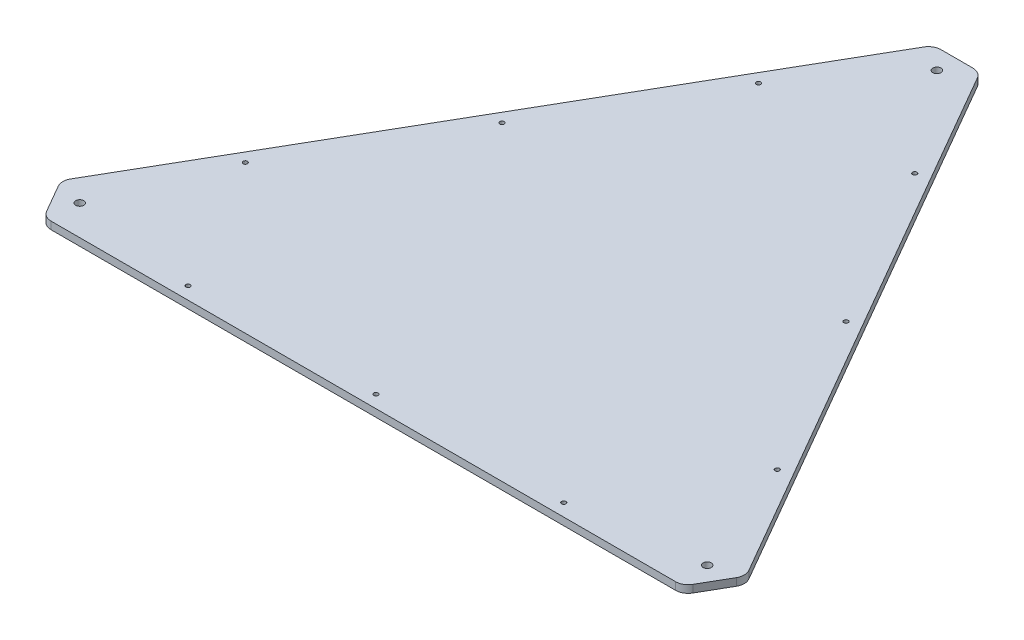
SolidWorks part; units mm, degrees
material "ABS"
ref_plane "Спереди" through (0, 0, 0) normal (0, 0, 1) x (1, 0, 0)
ref_plane "Сверху" through (0, 0, 0) normal (0, 1, 0) x (1, 0, 0)
ref_plane "Справа" through (0, 0, 0) normal (1, 0, 0) x (0, 0, -1)
sketch "Эскиз1" plane through (0, 0, 0) normal (0, 1, 0) x (1, 0, 0)
  line L17 (273.664, -136.638) -> (18.5, 305.319)
  line L18 (18.5, 305.319) -> (-18.5, 305.319)
  line L19 (-18.5, 305.319) -> (-273.664, -136.638)
  line L31 (-273.664, -136.638) -> (-255.164, -168.681)
  line L32 (-255.164, -168.681) -> (255.164, -168.681)
  line L33 (255.164, -168.681) -> (273.664, -136.638)
  line L34 (-264.414, -152.6595) -> (0, 0) construction
  line L35 (0, 0) -> (146.082, 84.3405) construction
  line L36 (264.414, -152.6595) -> (0, 0) construction
  line L37 (0, 0) -> (-146.082, 84.3405) construction
  line L38 (0, 305.319) -> (0, 0) construction
  line L39 (0, 0) -> (0, -168.681) construction
  circle A6 centre (0, 289.319) radius 3.25
  circle A7 centre (-250.5576, -144.6595) radius 3.25
  circle A8 centre (250.5576, -144.6595) radius 3.25
  point P3 (0, -168.681)
  point P11 (0, 305.319)
  dimension "D4" = 6.5
  dimension "D7" = 16
  dimension "D1" = 60
  dimension "D2" = 474
  dimension "D3" = 37
  dimension "D5" = 16
  dimension "D6" = 16
extrude "База" add sketch "Эскиз1" along normal mid plane 6
fillet "Скругление1" radius 10 6 edges at (273.664, 0, 136.638) (255.164, 0, 168.681) (-255.164, 0, 168.681) (-273.664, 0, 136.638) (18.5, 0, -305.319) (-18.5, 0, -305.319)
hole_wizard "К Профилю 3,2мм" positions "Эскиз2" profile "Эскиз3" hole size "Ø3.5" standard "DIN" end condition through all
sketch "Эскиз2" plane through (0, -3, 0) normal (0, -1, 0) x (-1, 0, 0)
  line L1 (150, -158.681) -> (0, -158.681) construction
  line L2 (0, -158.681) -> (-150, -158.681) construction
  line L5 (-212.4218, -50.5633) -> (-137.4218, 79.3405) construction
  line L6 (-137.4218, 79.3405) -> (-62.4218, 209.2443) construction
  line L9 (62.4218, 209.2443) -> (137.4218, 79.3405) construction
  line L10 (137.4218, 79.3405) -> (212.4218, -50.5633) construction
  line L19 (249.3905, -168.681) -> (-249.3905, -168.681) construction
  line L20 (21.3868, 300.319) -> (270.7773, -131.638) construction
  line L23 (137.4218, 79.3405) -> (-137.4218, 79.3405) construction
  line L24 (-137.4218, 79.3405) -> (0, -158.681) construction
  line L25 (0, -158.681) -> (137.4218, 79.3405) construction
  point P0 (150, -158.681)
  point P2 (0, -158.681)
  point P4 (-150, -158.681)
  point P6 (-212.4218, -50.5633)
  point P8 (-137.4218, 79.3405)
  point P10 (-62.4218, 209.2443)
  point P12 (62.4218, 209.2443)
  point P14 (137.4218, 79.3405)
  point P16 (212.4218, -50.5633)
  dimension "D1" = 10
  dimension "D2" = 10
  dimension "D3" = 60
  dimension "D4" = 60
  dimension "D5" = 300
sketch "Эскиз3" plane through (-150, -3, 158.681) normal (1, 0, 0) x (0, 0, -1)
  line L0 (0, 0) -> (0, 6)
  line L1 (0, 6) -> (1.75, 6)
  line L2 (1.75, 6) -> (1.75, 0)
  line L5 (1.75, 0) -> (0, 0)
  line L11 (0, -6.35) -> (0, 107.95) construction
  dimension "Диаметр сквозного отверстия" = 3.5
  dimension "Глубина сквозного отверстия" = 6
